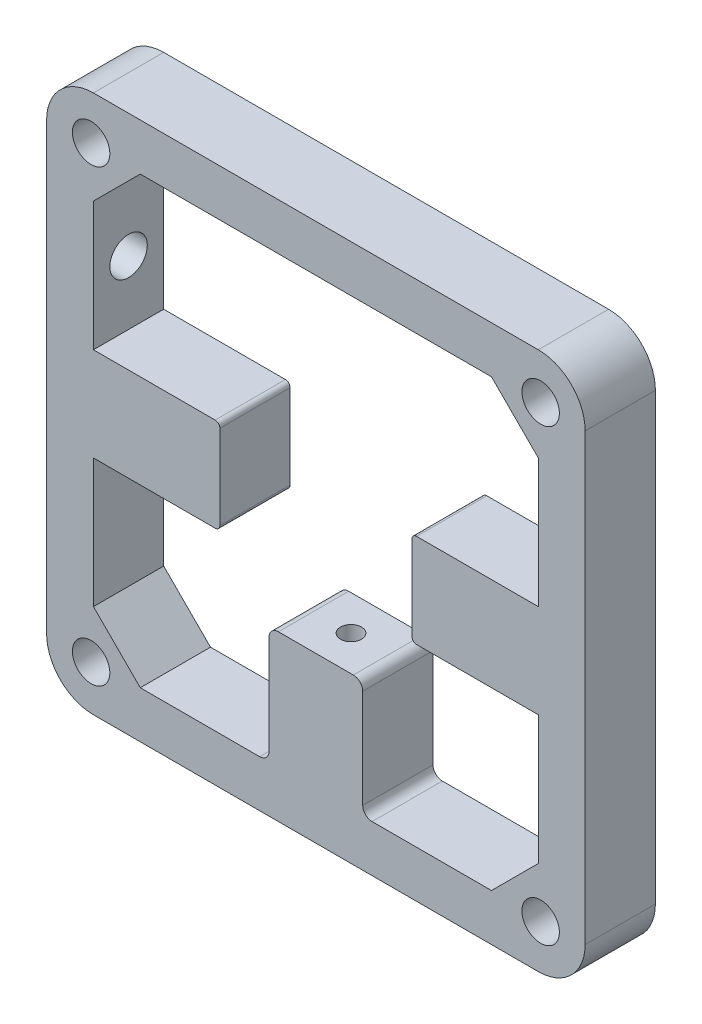
SolidWorks part; units mm, degrees
ref_plane "Front Plane" through (0, 0, 0) normal (0, 0, 1) x (1, 0, 0)
ref_plane "Top Plane" through (0, 0, 0) normal (0, 1, 0) x (1, 0, 0)
ref_plane "Right Plane" through (0, 0, 0) normal (1, 0, 0) x (0, 0, -1)
ref_plane "Plane1" through (0, -22.4, 0) normal (0, 1, 0) x (1, 0, 0)
ref_plane "Plane2" through (0, 0, -13) normal (0, 0, 1) x (1, 0, 0)
sketch "Sketch1" plane through (0, 0, -13) normal (0, 0, 1) x (1, 0, 0)
  line L1 (57.5, 57.5) -> (-57.5, 57.5)
  line L2 (57.5, 57.5) -> (57.5, -57.5)
  line L3 (57.5, -57.5) -> (-57.5, -57.5)
  line L4 (-57.5, 57.5) -> (-57.5, -57.5)
  line L5 (57.5, 57.5) -> (-57.5, -57.5) construction
  line L6 (57.5, -57.5) -> (-57.5, 57.5) construction
  line L7 (47.5, -47.5) -> (-47.5, -47.5)
  line L8 (47.5, -47.5) -> (47.5, 47.5)
  line L9 (47.5, 47.5) -> (-47.5, 47.5)
  line L10 (-47.5, -47.5) -> (-47.5, 47.5)
  line L11 (47.5, -47.5) -> (-47.5, 47.5) construction
  line L12 (47.5, 47.5) -> (-47.5, -47.5) construction
  point P0 (0, 0)
  point P6 (0, 0)
  dimension "D1" = 115
  dimension "D2" = 115
  dimension "D3" = 95
  dimension "D4" = 95
extrude "Boss-Extrude1" add sketch "Sketch1" along normal blind 15
sketch "Sketch10" plane through (0, -22.4, 0) normal (0, 1, 0) x (1, 0, 0)
  line L0 (0, 19.7027) -> (0, -12.8963) construction
  line L3 (-57.5, 5.5) -> (57.5, 5.5) construction
  line L4 (-57.5, -2) -> (-57.5, 13) construction
  line L5 (57.5, -2) -> (57.5, 13) construction
  line L6 (57.5, 13) -> (-57.5, 13) construction
  line L7 (10, -2) -> (-10, -2)
  line L8 (10, -2) -> (10, 13)
  line L9 (10, 13) -> (-10, 13)
  line L10 (-10, -2) -> (-10, 13)
  line L11 (10, -2) -> (-10, 13) construction
  line L12 (10, 13) -> (-10, -2) construction
  point P9 (0, 5.5)
  dimension "D1" = 20
extrude "Boss-Extrude4" add sketch "Sketch10" against normal blind 27
ref_plane "Plane3" through (0, -57.5, 0) normal (0, -1, 0) x (-1, 0, 0)
sketch "Sketch3" plane through (0, -57.5, 0) normal (0, -1, 0) x (-1, 0, 0)
  line L9 (-5.5, 10.5) -> (5.5, 10.5)
  line L10 (-5.5, 10.5) -> (-5.5, 0.5)
  line L11 (-5.5, 0.5) -> (5.5, 0.5)
  line L12 (5.5, 10.5) -> (5.5, 0.5)
  line L13 (-5.5, 10.5) -> (5.5, 0.5) construction
  line L14 (-5.5, 0.5) -> (5.5, 10.5) construction
  point P0 (0, 5.5)
  dimension "D1" = 5.5
  dimension "D2" = 11
  dimension "D3" = 10
extrude "Cut-Extrude1" cut sketch "Sketch3" against normal blind 28
fillet "Fillet1" radius 10 4 edges at (-57.5, -57.5, -5.5) (57.5, -57.5, -5.5) (57.5, 57.5, -5.5) (-57.5, 57.5, -5.5)
chamfer "Chamfer1" distance 10 angle 45 4 edges at (47.5, -47.5, -5.5) (-47.5, -47.5, -5.5) (47.5, 47.5, -5.5) (-47.5, 47.5, -5.5)
sketch "Sketch4" plane through (0, 0, 0) normal (0, 0, 1) x (1, 0, 0)
  line L0 (0, -14.3) -> (0, 14.3) construction
  line L1 (14.3, 0) -> (-14.3, 0) construction
  circle A0 centre (-48, 48) radius 4
  circle A1 centre (48, 48) radius 4
  circle A2 centre (48, -48) radius 4
  circle A3 centre (-48, -48) radius 4
extrude "Cut-Extrude3" cut sketch "Sketch4" against normal mid plane 115
sketch "Sketch5" plane through (0, 0, 0) normal (0, 0, 1) x (1, 0, 0)
  line L0 (-47.5, 37.5) -> (-47.5, -37.5) construction
  line L1 (47.5, 10) -> (-47.5, 10)
  line L2 (47.5, 10) -> (47.5, -10)
  line L3 (47.5, -10) -> (-47.5, -10)
  line L4 (-47.5, 10) -> (-47.5, -10)
  line L5 (47.5, 10) -> (-47.5, -10) construction
  line L6 (47.5, -10) -> (-47.5, 10) construction
  point P0 (0, 0)
  dimension "D1" = 20
extrude "Boss-Extrude3" [suppressed] add sketch "Sketch5" along normal mid plane 13.5
ref_plane "Plane4" through (0, 0, 2) normal (0, 0, 1) x (1, 0, 0)
sketch "Sketch6" plane through (0, 0, 2) normal (0, 0, 1) x (1, 0, 0)
  line L1 (21, 15) -> (-21, 15)
  line L2 (21, 15) -> (21, -15)
  line L3 (21, -15) -> (-21, -15)
  line L4 (-21, 15) -> (-21, -15)
  line L5 (21, 15) -> (-21, -15) construction
  line L6 (21, -15) -> (-21, 15) construction
  point P0 (0, 0)
  dimension "D1" = 42
  dimension "D2" = 30
extrude "Cut-Extrude4" [suppressed] cut sketch "Sketch6" against normal blind 30
ref_plane "Plane5" through (57.5, 0, 0) normal (1, 0, 0) x (0, 0, -1)
sketch "Sketch7" plane through (57.5, 0, 0) normal (1, 0, 0) x (0, 0, -1)
  circle A0 centre (30, 0) radius 25
  dimension "D2" = 50
  dimension "D1" = 30
extrude "Cut-Extrude5" [suppressed] cut sketch "Sketch7" against normal through all
sketch "Sketch8" plane through (57.5, 0, 0) normal (1, 0, 0) x (0, 0, -1)
  line L1 (5, 10) -> (25, 10)
  line L2 (5, 10) -> (5, -10)
  line L3 (5, -10) -> (25, -10)
  line L4 (25, 10) -> (25, -10)
  line L5 (5, 10) -> (25, -10) construction
  line L6 (5, -10) -> (25, 10) construction
  point P0 (15, 0)
  dimension "D1" = 15
  dimension "D2" = 20
  dimension "D3" = 20
extrude "Cut-Extrude6" [suppressed] cut sketch "Sketch8" against normal through all
fillet "Fillet3" [suppressed] radius 2
ref_plane "Plane6" through (-57.5, 0, 0) normal (-1, 0, 0) x (0, 0, 1)
sketch "Sketch9" plane through (-57.5, 0, 0) normal (-1, 0, 0) x (0, 0, 1)
  circle A0 centre (-5.5, 23.6) radius 4
  dimension "D1" = 8
  dimension "D2" = 5.5
  dimension "D3" = 23.6
extrude "Cut-Extrude7" cut sketch "Sketch9" against normal blind 30
fillet "Fillet4" [suppressed] radius 2
fillet "Fillet6" radius 2 4 edges at (-10, -47.5, -5.5) (10, -47.5, -5.5) (10, -22.4, -5.5) (-10, -22.4, -5.5)
ref_plane "Plane7" through (0, -29.5, 0) normal (0, -1, 0) x (-1, 0, 0)
sketch "Sketch11" plane through (0, -29.5, 0) normal (0, -1, 0) x (-1, 0, 0)
  line L6 (-5.5, 5.5) -> (5.5, 5.5) construction
  line L7 (-5.5, 10.5) -> (-5.5, 0.5) construction
  line L8 (5.5, 0.5) -> (5.5, 10.5) construction
  line L9 (0, 10.5) -> (0, 0.5) construction
  line L10 (5.5, 10.5) -> (-5.5, 10.5) construction
  line L11 (-5.5, 0.5) -> (5.5, 0.5) construction
  circle A3 centre (0, 5.5) radius 2.25
  dimension "D1" = 4.5
extrude "Cut-Extrude8" cut sketch "Sketch11" against normal blind 30
sketch "Sketch12" plane through (0, 0, 2) normal (0, 0, 1) x (1, 0, 0)
  line L1 (47.5, -10) -> (-47.5, -10)
  line L2 (47.5, -10) -> (47.5, 10)
  line L3 (47.5, 10) -> (-47.5, 10)
  line L4 (-47.5, -10) -> (-47.5, 10)
  line L5 (47.5, -10) -> (-47.5, 10) construction
  line L6 (47.5, 10) -> (-47.5, -10) construction
  point P0 (0, 0)
  dimension "D1" = 20
  dimension "D2" = 95
extrude "Boss-Extrude5" add sketch "Sketch12" against normal blind 15
sketch "Sketch13" plane through (0, 0, 2) normal (0, 0, 1) x (1, 0, 0)
  line L1 (-20.5, 13.9078) -> (20.5, 13.9078)
  line L2 (-20.5, 13.9078) -> (-20.5, -13.9078)
  line L3 (-20.5, -13.9078) -> (20.5, -13.9078)
  line L4 (20.5, 13.9078) -> (20.5, -13.9078)
  line L5 (-20.5, 13.9078) -> (20.5, -13.9078) construction
  line L6 (-20.5, -13.9078) -> (20.5, 13.9078) construction
  point P0 (0, 0)
  dimension "D1" = 41
extrude "Cut-Extrude9" cut sketch "Sketch13" against normal blind 20
fillet "Fillet7" radius 1 4 edges at (20.5, -10, -5.5) (20.5, 10, -5.5) (-20.5, -10, -5.5) (-20.5, 10, -5.5)
